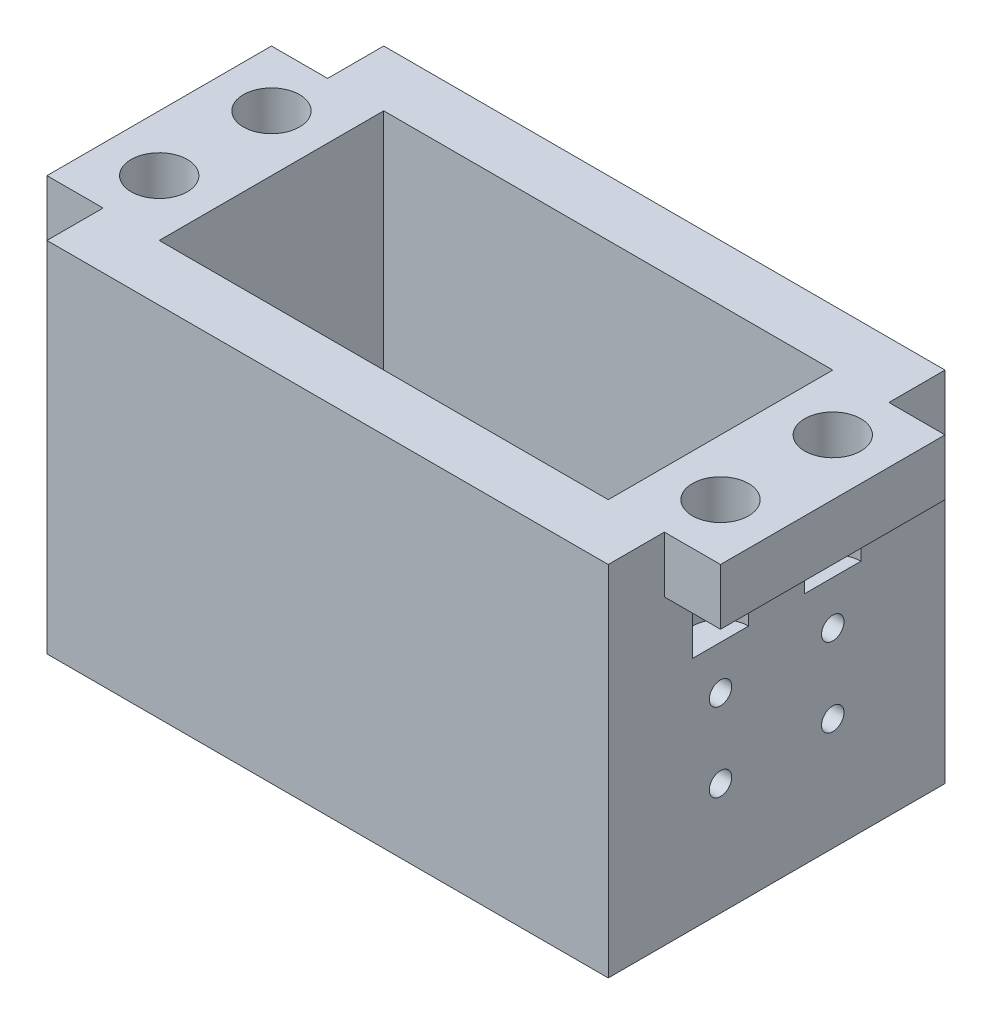
SolidWorks part; units mm, degrees
ref_plane "Front Plane" through (0, 0, 0) normal (0, 0, 1) x (1, 0, 0)
ref_plane "Top Plane" through (0, 0, 0) normal (0, 1, 0) x (1, 0, 0)
ref_plane "Right Plane" through (0, 0, 0) normal (1, 0, 0) x (0, 0, -1)
sketch "Sketch1" plane through (0, 0, 0) normal (0, 1, 0) x (1, 0, 0)
  line L0 (25, 15) -> (-25, 15)
  line L1 (20, -10) -> (-20, -10)
  line L2 (20, -10) -> (20, 10)
  line L3 (20, 10) -> (-20, 10)
  line L4 (-20, -10) -> (-20, 10)
  line L5 (20, -10) -> (-20, 10) construction
  line L6 (20, 10) -> (-20, -10) construction
  line L7 (-25, -15) -> (-25, 15)
  line L8 (25, -15) -> (-25, -15)
  line L9 (25, -15) -> (25, 15)
  point P0 (0, 0)
  dimension "D1" = 5
  dimension "D2" = 50
extrude "Boss-Extrude1" add sketch "Sketch1" along normal blind 26.9
sketch "Sketch2" plane through (0, 26.9, 0) normal (0, 1, 0) x (1, 0, 0)
  line L0 (20, 0) -> (25, 0) construction
  line L1 (20, 10) -> (30, 10)
  line L2 (20, 10) -> (20, -10)
  line L3 (20, -10) -> (30, -10)
  line L4 (30, 10) -> (30, -10)
  line L5 (25, 0) -> (25, 5) construction
  line L6 (25, -15) -> (25, 15) construction
  line L7 (25, 0) -> (25, -5) construction
  line L8 (0, 10) -> (0, -5) construction
  line L9 (20, 10) -> (-20, 10) construction
  line L10 (-20, -10) -> (-30, -10)
  line L11 (-30, 10) -> (-30, -10)
  line L12 (-20, 10) -> (-30, 10)
  line L13 (-20, 10) -> (-20, -10)
  circle A0 centre (25, 5) radius 2.5
  circle A1 centre (25, -5) radius 2.5
  circle A2 centre (-25, -5) radius 2.5
  circle A3 centre (-25, 5) radius 2.5
  dimension "D1" = 5
  dimension "D2" = 5
extrude "Boss-Extrude2" add sketch "Sketch2" against normal blind 5
sketch "Sketch3" plane through (0, 26.9, 0) normal (0, 1, 0) x (1, 0, 0)
  line L0 (-25, 7.5) -> (-25, 2.5) construction
  line L1 (-25, -2.5) -> (-25, -7.5) construction
  line L2 (25, -7.5) -> (25, -2.5) construction
  line L3 (25, 2.5) -> (25, 7.5) construction
  circle A0 centre (-25, 5) radius 2.5
  circle A1 centre (-25, -5) radius 2.5
  circle A2 centre (25, -5) radius 2.5
  circle A3 centre (25, 5) radius 2.5
extrude "Cut-Extrude1" cut sketch "Sketch3" against normal blind 11
sketch "Sketch5" plane through (20, 0, 0) normal (-1, 0, 0) x (0, 0, 1)
  line L0 (0, 0) -> (0, 5) construction
  line L1 (0, 5) -> (-5, 5)
  line L2 (0, 5) -> (5, 5) construction
  line L3 (0, 5) -> (0, 12) construction
  line L4 (0, 12) -> (-5, 12) construction
  line L5 (0, 12) -> (5, 12) construction
  circle A0 centre (-5, 12) radius 1.5
  circle A1 centre (-5, 5) radius 1.5
  circle A2 centre (5, 12) radius 1.5
  circle A3 centre (5, 5) radius 1.5
extrude "Cut-Extrude3" cut sketch "Sketch5" against normal blind 3
sketch "Sketch6" plane through (23, 0, 0) normal (-1, 0, 0) x (0, 0, 1)
  circle A0 centre (-5, 12) radius 1
  circle A1 centre (5, 12) radius 1
  circle A2 centre (-5, 5) radius 1
  circle A3 centre (5, 5) radius 1
extrude "Cut-Extrude4" cut sketch "Sketch6" against normal blind 9
sketch "Sketch7" plane through (0, 0, 0) normal (0, -1, 0) x (1, 0, 0)
  line L4 (25, -15) -> (25, 15)
  line L5 (25, 15) -> (-25, 15)
  line L6 (-25, 15) -> (-25, -15)
  line L7 (-25, -15) -> (25, -15)
  line L8 (25, -15) -> (25, 15)
  line L9 (25, 15) -> (-25, 15)
  line L10 (-25, 15) -> (-25, -15)
  line L11 (-25, -15) -> (25, -15)
  dimension "D1" = 0
extrude "Boss-Extrude3" add sketch "Sketch7" along normal blind 5
